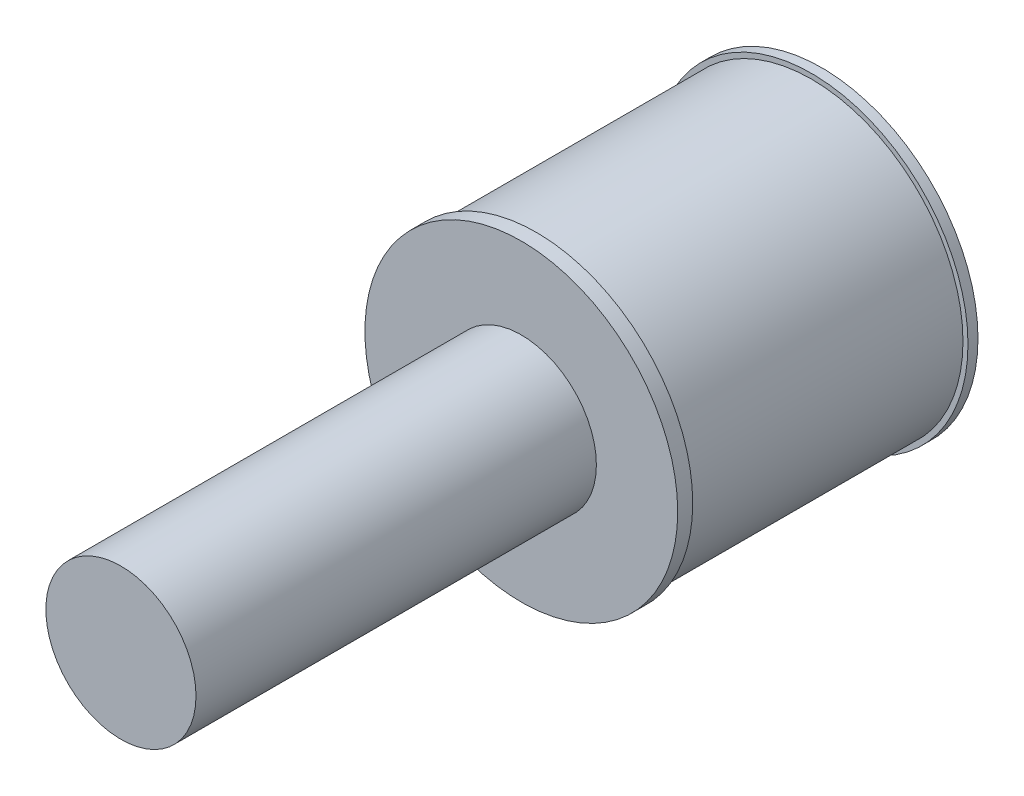
SolidWorks part; units mm, degrees
ref_plane "Front Plane" through (0, 0, 0) normal (0, 0, 1) x (1, 0, 0)
ref_plane "Top Plane" through (0, 0, 0) normal (0, 1, 0) x (1, 0, 0)
ref_plane "Right Plane" through (0, 0, 0) normal (1, 0, 0) x (0, 0, -1)
sketch "S01 - Retaining flange" plane through (0, 0, 0) normal (0, 0, 1) x (1, 0, 0)
  circle A0 centre (0, 0) radius 6.25
  dimension "D1" = 12.5
extrude "01 - Retaining flange" add sketch "S01 - Retaining flange" along normal blind 0.4
sketch "S02 - Inner race and sealed rolling assembly envelope" plane through (0, 0, 0) normal (0, 0, 1) x (1, 0, 0)
  circle A0 centre (0, 0) radius 6.05
  dimension "D1" = 12.1
extrude "02 - Inner race and sealed rolling assembly envelope" add sketch "S02 - Inner race and sealed rolling assembly envelope" along normal blind 11 from offset 0.4
sketch "S03 - Mounting thrust face" plane through (0, 0, 0) normal (0, 0, 1) x (1, 0, 0)
  circle A0 centre (0, 0) radius 6.25
  dimension "D1" = 12.5
extrude "03 - Mounting thrust face" add sketch "S03 - Mounting thrust face" along normal blind 0.6 from offset 11.4
sketch "S04 - Six millimetre stud with final 8 mm M6 thread envelope" plane through (0, 0, 0) normal (0, 0, 1) x (1, 0, 0)
  circle A0 centre (0, 0) radius 3
  dimension "D1" = 6
extrude "04 - Six millimetre stud with final 8 mm M6 thread envelope" add sketch "S04 - Six millimetre stud with final 8 mm M6 thread envelope" along normal blind 16 from offset 12
sketch "S05 - Assembly drive slot" plane through (0, 0, 0) normal (0, 0, 1) x (1, 0, 0)
  line L0 (-4.2, -0.7) -> (4.2, -0.7)
  line L1 (4.2, -0.7) -> (4.2, 0.7)
  line L2 (4.2, 0.7) -> (-4.2, 0.7)
  line L3 (-4.2, 0.7) -> (-4.2, -0.7)
  dimension "D1" = 4.2
  dimension "D2" = 4.2
  dimension "D3" = 0.7
  dimension "D4" = 0.7
extrude "05 - Assembly drive slot" cut sketch "S05 - Assembly drive slot" along normal blind 0.7 from offset 0.1
